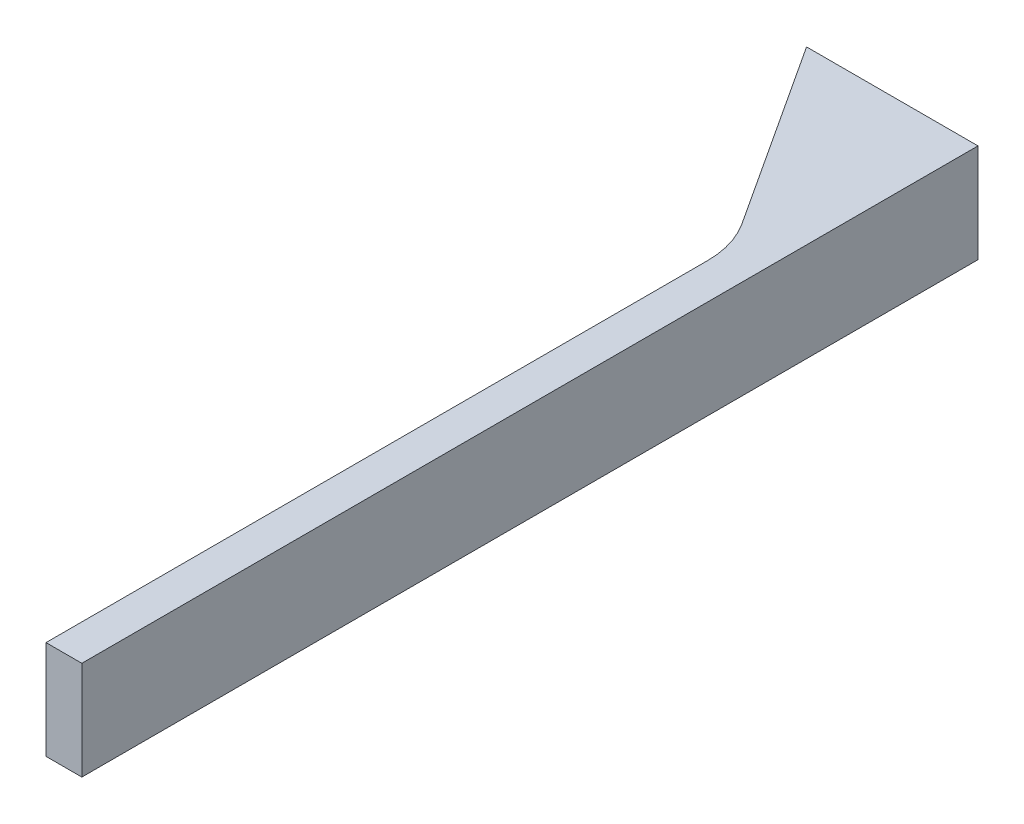
SolidWorks part; units mm, degrees
ref_plane "Alzado" through (0, 0, 0) normal (0, 0, 1) x (1, 0, 0)
ref_plane "Planta" through (0, 0, 0) normal (0, 1, 0) x (1, 0, 0)
ref_plane "Vista lateral" through (0, 0, 0) normal (1, 0, 0) x (0, 0, -1)
sketch "Croquis1" plane through (0, 0, 0) normal (0, 0, 1) x (1, 0, 0)
  line L0 (-11, -5.5) -> (-15, -5.5) construction
  line L1 (-11, 5.5) -> (-11, -5.5) construction
  line L2 (-15, 5.5) -> (-11, 5.5) construction
  line L3 (-11, -5.5) -> (-15, -5.5)
  line L4 (-11, 5.5) -> (-11, -5.5)
  line L5 (-15, 5.5) -> (-11, 5.5)
  line L6 (-15, -5.5) -> (-15, 5.5)
extrude "Saliente-Extruir1" add sketch "Croquis1" against normal blind 100
sketch "Croquis3" plane through (0, -5.5, 0) normal (0, -1, 0) x (1, 0, 0)
  line L0 (-15, -100) -> (-30.131, -100)
  line L2 (-30.131, -100) -> (-15, -76.7825)
  line L3 (-15, -100) -> (-15, 0) construction
  line L4 (-15, -100) -> (-15, -76.7825)
extrude "Saliente-Extruir2" add sketch "Croquis3" against normal up to surface (11 mm away) up to face at (-13, 5.5, -50)
fillet "Redondeo1" radius 10 1 edges at (-15, 0, -76.7825)
